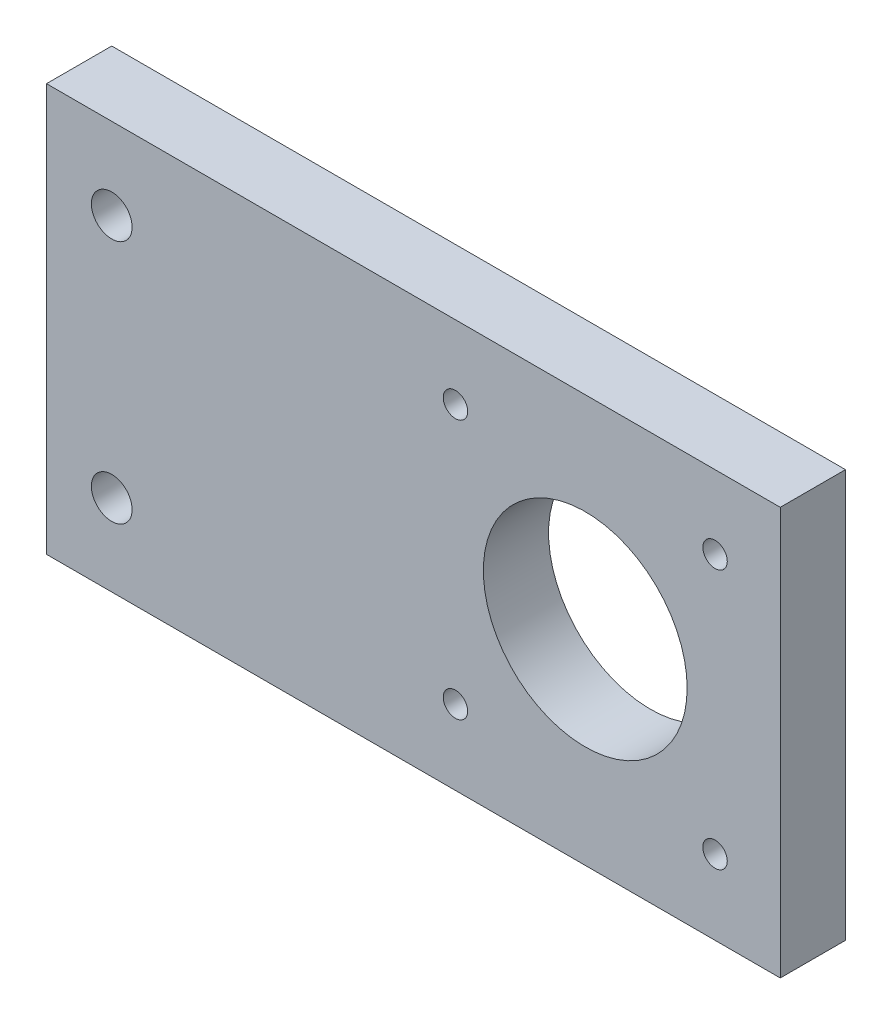
SolidWorks part; units mm, degrees
ref_plane "Front Plane" through (0, 0, 0) normal (0, 0, 1) x (1, 0, 0)
ref_plane "Top Plane" through (0, 0, 0) normal (0, 1, 0) x (1, 0, 0)
ref_plane "Right Plane" through (0, 0, 0) normal (1, 0, 0) x (0, 0, -1)
sketch "Sketch1" plane through (0, 0, 0) normal (0, 0, 1) x (1, 0, 0)
  line L1 (-45, -25) -> (45, -25)
  line L2 (-45, -25) -> (-45, 25)
  line L3 (-45, 25) -> (45, 25)
  line L4 (45, -25) -> (45, 25)
  line L5 (-45, -25) -> (45, 25) construction
  line L6 (-45, 25) -> (45, -25) construction
  point P0 (0, 0)
  dimension "D1" = 90
  dimension "D2" = 50
extrude "Boss-Extrude1" add sketch "Sketch1" along normal blind 8
sketch "Sketch2" plane through (0, 0, 8) normal (0, 0, 1) x (1, 0, 0)
  line L0 (45, -25) -> (45, 25) construction
  line L1 (45, 25) -> (-45, 25) construction
  line L2 (5.16, 16) -> (37, -15.84) construction
  line L3 (5.16, -15.84) -> (37, 16) construction
  line L4 (-45, 25) -> (-45, -25) construction
  line L5 (-45, -25) -> (45, -25) construction
  circle A0 centre (37, 16) radius 1.5
  circle A1 centre (37, -15.84) radius 1.5
  circle A2 centre (5.16, -15.84) radius 1.5
  circle A3 centre (5.16, 16) radius 1.5
  circle A4 centre (21.08, 0.08) radius 12.5
  circle A5 centre (-37, 15) radius 2.5
  circle A6 centre (-37, -15) radius 2.5
  dimension "D1" = 3
  dimension "D2" = 3
  dimension "D3" = 3
  dimension "D4" = 3
  dimension "D5" = 31.84
  dimension "D6" = 31.84
  dimension "D7" = 31.84
  dimension "D8" = 31.84
  dimension "D9" = 8
  dimension "D10" = 9
  dimension "D11" = 25
  dimension "D12" = 5
  dimension "D13" = 5
  dimension "D14" = 10
  dimension "D15" = 8
  dimension "D16" = 10
extrude "Cut-Extrude1" cut sketch "Sketch2" against normal blind 8 contours A4 | A1 | A6 | A2 | A0 | A3 | A5
